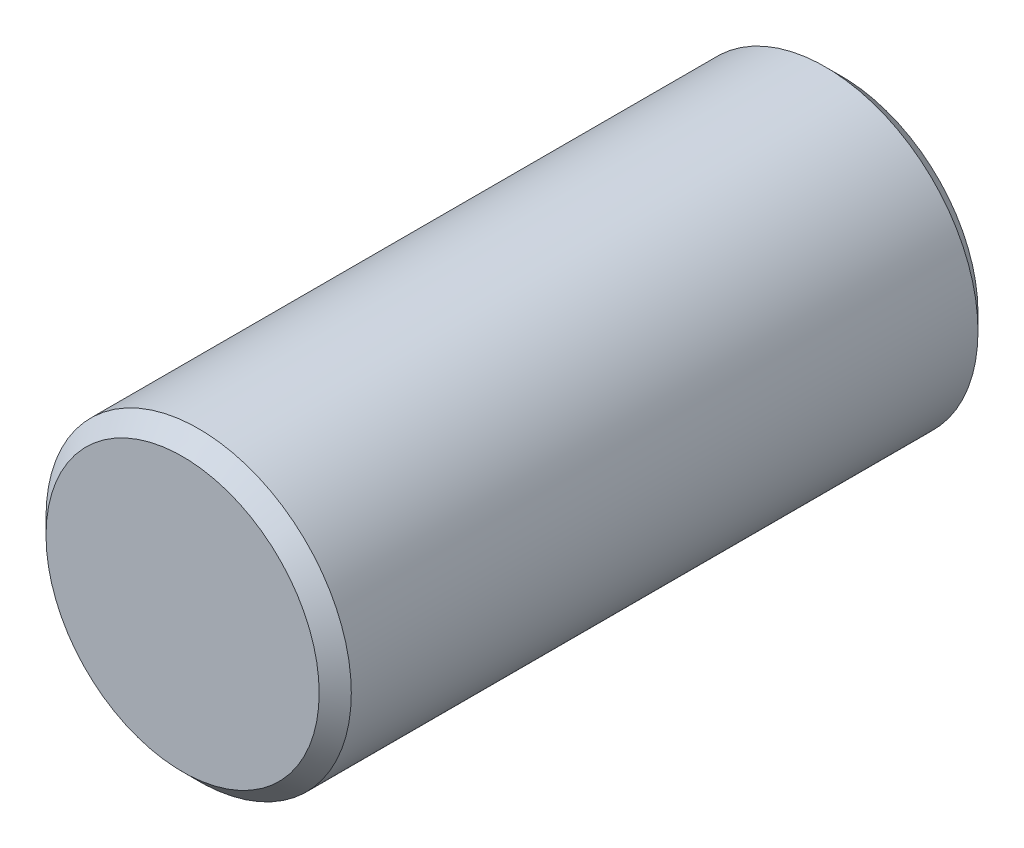
SolidWorks part; units mm, degrees
ref_plane "Front Plane" through (0, 0, 0) normal (0, 0, 1) x (1, 0, 0)
ref_plane "Top Plane" through (0, 0, 0) normal (0, 1, 0) x (1, 0, 0)
ref_plane "Right Plane" through (0, 0, 0) normal (1, 0, 0) x (0, 0, -1)
sketch "Sketch1" plane through (0, 0, 0) normal (0, 0, 1) x (1, 0, 0)
  circle A0 centre (0, 0) radius 19
  dimension "D1" = 38
extrude "Boss-Extrude1" add sketch "Sketch1" along normal mid plane 82
chamfer "Chamfer1" distance 2 angle 45 2 edges at (19, 0, -41) (19, 0, 41)
